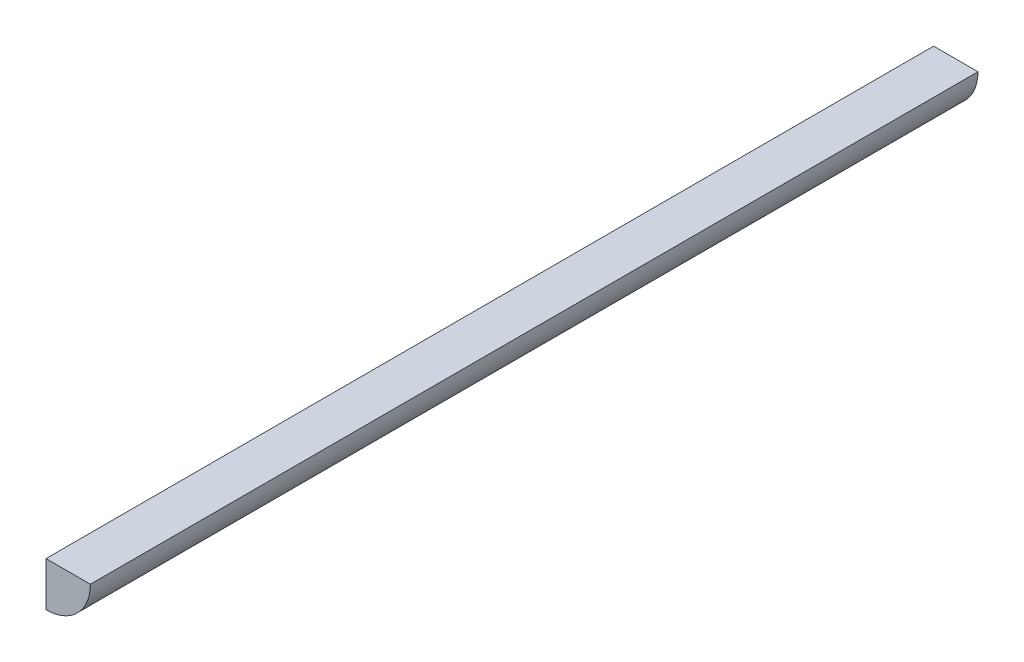
SolidWorks part; units mm, degrees
ref_plane "Front Plane" through (0, 0, 0) normal (0, 0, 1) x (1, 0, 0)
ref_plane "Top Plane" through (0, 0, 0) normal (0, 1, 0) x (1, 0, 0)
ref_plane "Right Plane" through (0, 0, 0) normal (1, 0, 0) x (0, 0, -1)
sketch "Sketch1" plane through (0, 0, 0) normal (0, 0, 1) x (1, 0, 0)
  line L0 (0, 0) -> (20, 0)
  line L1 (0, -20) -> (0, 0)
  arc A0 (20, 0) -> (0, -20) centre (0, 0) cw
  dimension "D1" = 20
extrude "Boss-Extrude1" add sketch "Sketch1" along normal mid plane 400
